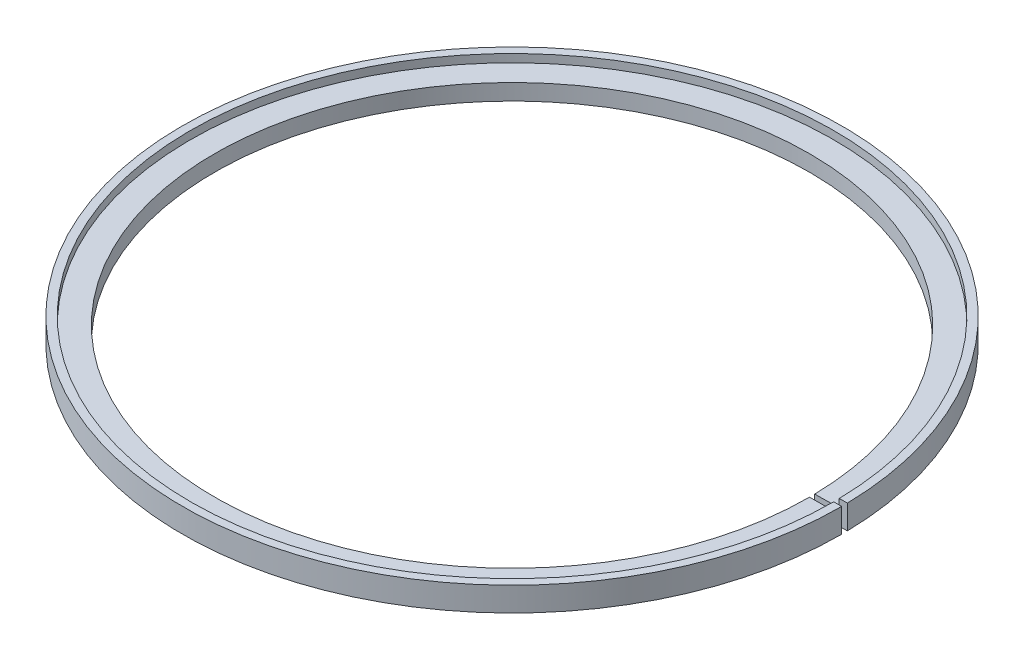
SolidWorks part; units mm, degrees
ref_plane "前视基准面" through (0, 0, 0) normal (0, 0, 1) x (1, 0, 0)
ref_plane "上视基准面" through (0, 0, 0) normal (0, 1, 0) x (1, 0, 0)
ref_plane "右视基准面" through (0, 0, 0) normal (1, 0, 0) x (0, 0, -1)
sketch "草图1" plane through (0, 0, 0) normal (0, 0, 1) x (1, 0, 0)
  line L0 (0, 10) -> (0, -10) construction
  line L1 (40, 3) -> (41, 3)
  line L2 (37, 2) -> (40, 2)
  line L3 (37, 2) -> (37, 0)
  line L4 (37, 0) -> (41, 0)
  line L5 (41, 3) -> (41, 0)
  line L6 (40, 3) -> (40, 2)
  dimension "D1" = 37
  dimension "D2" = 41
  dimension "D3" = 2
  dimension "D4" = 3
  dimension "D5" = 40
revolve "旋转1" add sketch "草图1" angle 359 about L0
